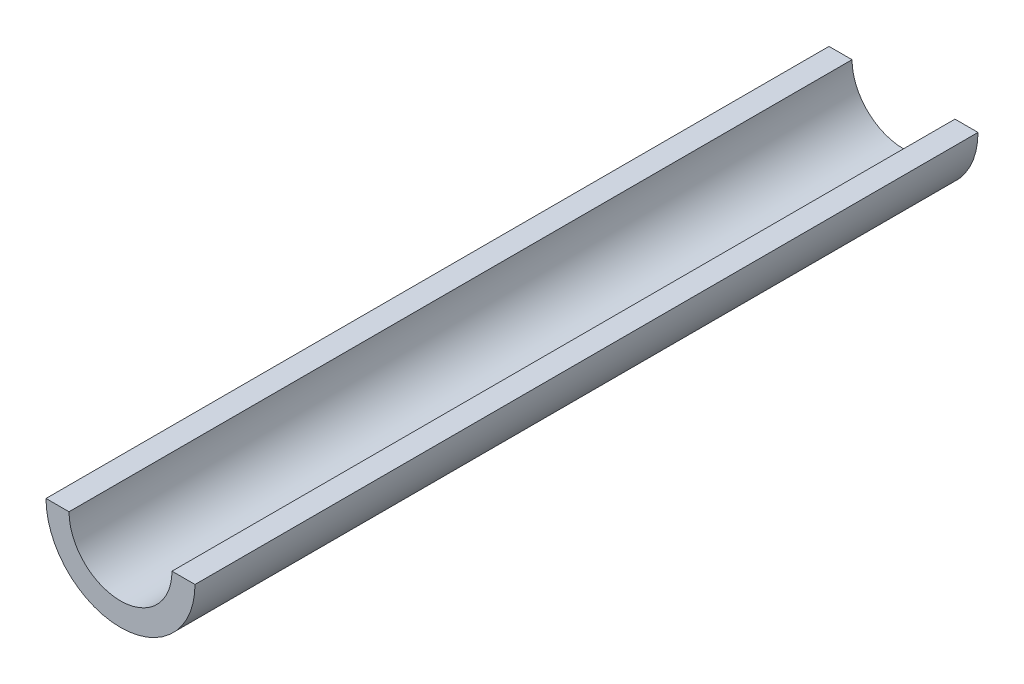
SolidWorks part; units mm, degrees
ref_plane "Front Plane" through (0, 0, 0) normal (0, 0, 1) x (1, 0, 0)
ref_plane "Top Plane" through (0, 0, 0) normal (0, 1, 0) x (1, 0, 0)
ref_plane "Right Plane" through (0, 0, 0) normal (1, 0, 0) x (0, 0, -1)
sketch "Sketch1" plane through (0, 0, 0) normal (0, 0, 1) x (1, 0, 0)
  line L0 (-16.175, 0) -> (-11.175, 0)
  line L1 (11.175, 0) -> (16.175, 0)
  arc A0 (-11.175, 0) -> (11.175, 0) centre (0, 0) ccw
  arc A1 (-16.175, 0) -> (16.175, 0) centre (0, 0) ccw
  circle A3 centre (0, 0) radius 11.175 construction
  circle A4 centre (0, 0) radius 16.175 construction
  point P1 (16.175, 0)
  point P7 (10.6867, 3.2673)
  dimension "D1" = 22.35
  dimension "D2" = 5
extrude "Boss-Extrude1" add sketch "Sketch1" along normal blind 170
